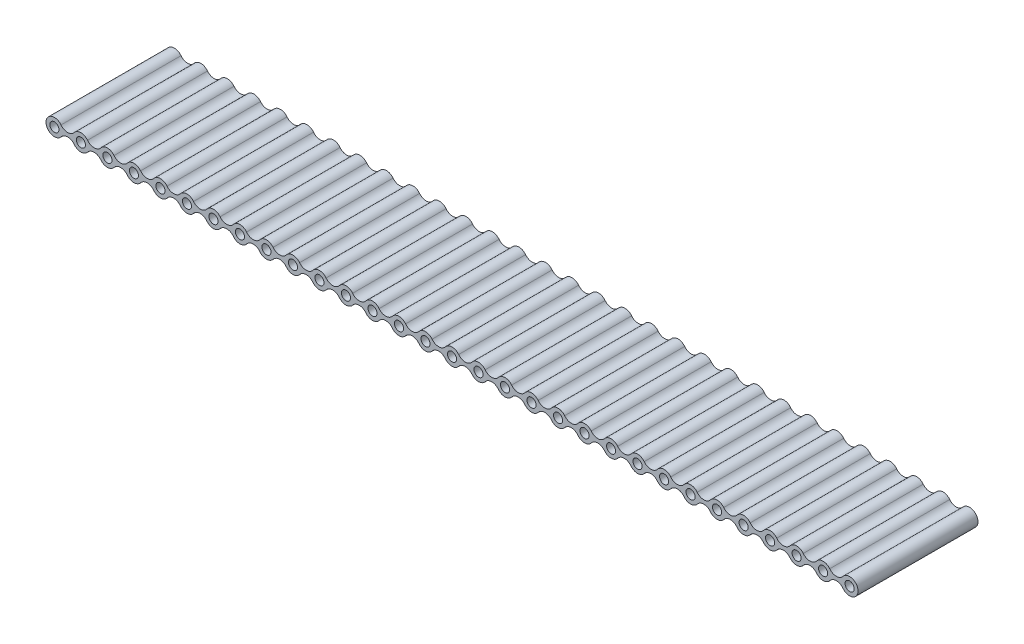
SolidWorks part; units mm, degrees
ref_plane "Front Plane" through (0, 0, 0) normal (0, 0, 1) x (1, 0, 0)
ref_plane "Top Plane" through (0, 0, 0) normal (0, 1, 0) x (1, 0, 0)
ref_plane "Right Plane" through (0, 0, 0) normal (1, 0, 0) x (0, 0, -1)
sketch "Sketch1" plane through (0, 0, 0) normal (0, 0, 1) x (1, 0, 0)
  line L0 (-3.1044, -11.0303) -> (166.8956, -11.0303) construction
  arc A0 (1.3809, 1.075) -> (1.3809, -1.075) centre (0, 0) ccw
  circle A1 centre (0, 0) radius 0.95
  arc A2 (4.1427, -1.075) -> (6.9045, -1.075) centre (5.5236, 0) ccw
  circle A3 centre (5.5236, 0) radius 0.95
  arc A4 (9.6663, -1.075) -> (12.4281, -1.075) centre (11.0472, 0) ccw
  circle A5 centre (11.0472, 0) radius 0.95
  arc A6 (15.1899, -1.075) -> (17.9517, -1.075) centre (16.5708, 0) ccw
  circle A7 centre (16.5708, 0) radius 0.95
  arc A8 (20.7134, -1.075) -> (23.4752, -1.075) centre (22.0943, 0) ccw
  circle A9 centre (22.0943, 0) radius 0.95
  arc A10 (26.237, -1.075) -> (28.9988, -1.075) centre (27.6179, 0) ccw
  circle A11 centre (27.6179, 0) radius 0.95
  arc A12 (31.7606, -1.075) -> (34.5224, -1.075) centre (33.1415, 0) ccw
  circle A13 centre (33.1415, 0) radius 0.95
  arc A14 (37.2842, -1.075) -> (40.046, -1.075) centre (38.6651, 0) ccw
  circle A15 centre (38.6651, 0) radius 0.95
  arc A16 (42.8078, -1.075) -> (45.5696, -1.075) centre (44.1887, 0) ccw
  circle A17 centre (44.1887, 0) radius 0.95
  arc A18 (48.3314, -1.075) -> (51.0932, -1.075) centre (49.7123, 0) ccw
  circle A19 centre (49.7123, 0) radius 0.95
  arc A20 (1.3809, 1.075) -> (4.1427, 1.075) centre (2.7618, 2.15) ccw
  arc A21 (1.3809, -1.075) -> (4.1427, -1.075) centre (2.7618, -2.15) cw
  arc A22 (6.9045, 1.075) -> (9.6663, 1.075) centre (8.2854, 2.15) ccw
  arc A23 (6.9045, -1.075) -> (9.6663, -1.075) centre (8.2854, -2.15) cw
  arc A24 (12.4281, 1.075) -> (15.1899, 1.075) centre (13.809, 2.15) ccw
  arc A25 (12.4281, -1.075) -> (15.1899, -1.075) centre (13.809, -2.15) cw
  arc A26 (17.9517, 1.075) -> (20.7134, 1.075) centre (19.3326, 2.15) ccw
  arc A27 (17.9517, -1.075) -> (20.7134, -1.075) centre (19.3326, -2.15) cw
  arc A28 (23.4752, 1.075) -> (26.237, 1.075) centre (24.8561, 2.15) ccw
  arc A29 (23.4752, -1.075) -> (26.237, -1.075) centre (24.8561, -2.15) cw
  arc A30 (28.9988, 1.075) -> (31.7606, 1.075) centre (30.3797, 2.15) ccw
  arc A31 (28.9988, -1.075) -> (31.7606, -1.075) centre (30.3797, -2.15) cw
  arc A32 (34.5224, 1.075) -> (37.2842, 1.075) centre (35.9033, 2.15) ccw
  arc A33 (34.5224, -1.075) -> (37.2842, -1.075) centre (35.9033, -2.15) cw
  arc A34 (40.046, 1.075) -> (42.8078, 1.075) centre (41.4269, 2.15) ccw
  arc A35 (40.046, -1.075) -> (42.8078, -1.075) centre (41.4269, -2.15) cw
  arc A36 (45.5696, 1.075) -> (48.3314, 1.075) centre (46.9505, 2.15) ccw
  arc A37 (45.5696, -1.075) -> (48.3314, -1.075) centre (46.9505, -2.15) cw
  arc A38 (53.855, -1.075) -> (56.6168, -1.075) centre (55.2359, 0) ccw
  circle A39 centre (55.2359, 0) radius 0.95
  arc A40 (59.3785, -1.075) -> (62.1403, -1.075) centre (60.7594, 0) ccw
  circle A41 centre (60.7594, 0) radius 0.95
  arc A42 (64.9021, -1.075) -> (67.6639, -1.075) centre (66.283, 0) ccw
  circle A43 centre (66.283, 0) radius 0.95
  arc A44 (70.4257, -1.075) -> (73.1875, -1.075) centre (71.8066, 0) ccw
  circle A45 centre (71.8066, 0) radius 0.95
  arc A46 (75.9493, -1.075) -> (78.7111, -1.075) centre (77.3302, 0) ccw
  circle A47 centre (77.3302, 0) radius 0.95
  arc A48 (81.4729, -1.075) -> (84.2347, -1.075) centre (82.8538, 0) ccw
  circle A49 centre (82.8538, 0) radius 0.95
  arc A50 (86.9965, -1.075) -> (89.7583, -1.075) centre (88.3774, 0) ccw
  circle A51 centre (88.3774, 0) radius 0.95
  arc A52 (92.5201, -1.075) -> (95.2819, -1.075) centre (93.901, 0) ccw
  circle A53 centre (93.901, 0) radius 0.95
  arc A54 (98.0436, -1.075) -> (100.8054, -1.075) centre (99.4245, 0) ccw
  circle A55 centre (99.4245, 0) radius 0.95
  arc A56 (103.5672, -1.075) -> (106.329, -1.075) centre (104.9481, 0) ccw
  circle A57 centre (104.9481, 0) radius 0.95
  arc A58 (109.0908, -1.075) -> (111.8526, -1.075) centre (110.4717, 0) ccw
  circle A59 centre (110.4717, 0) radius 0.95
  arc A60 (114.6144, -1.075) -> (117.3762, -1.075) centre (115.9953, 0) ccw
  circle A61 centre (115.9953, 0) radius 0.95
  arc A62 (120.138, -1.075) -> (122.8998, -1.075) centre (121.5189, 0) ccw
  circle A63 centre (121.5189, 0) radius 0.95
  arc A64 (125.6616, -1.075) -> (128.4234, -1.075) centre (127.0425, 0) ccw
  circle A65 centre (127.0425, 0) radius 0.95
  arc A66 (131.1852, -1.075) -> (133.947, -1.075) centre (132.5661, 0) ccw
  circle A67 centre (132.5661, 0) radius 0.95
  arc A68 (136.7087, -1.075) -> (139.4705, -1.075) centre (138.0896, 0) ccw
  circle A69 centre (138.0896, 0) radius 0.95
  arc A70 (142.2323, -1.075) -> (144.9941, -1.075) centre (143.6132, 0) ccw
  circle A71 centre (143.6132, 0) radius 0.95
  arc A72 (147.7559, -1.075) -> (150.5177, -1.075) centre (149.1368, 0) ccw
  circle A73 centre (149.1368, 0) radius 0.95
  arc A74 (153.2795, -1.075) -> (156.0413, -1.075) centre (154.6604, 0) ccw
  circle A75 centre (154.6604, 0) radius 0.95
  arc A76 (51.0932, 1.075) -> (53.855, 1.075) centre (52.4741, 2.15) ccw
  arc A77 (51.0932, -1.075) -> (53.855, -1.075) centre (52.4741, -2.15) cw
  arc A78 (56.6168, 1.075) -> (59.3785, 1.075) centre (57.9977, 2.15) ccw
  arc A79 (56.6168, -1.075) -> (59.3785, -1.075) centre (57.9977, -2.15) cw
  arc A80 (62.1403, 1.075) -> (64.9021, 1.075) centre (63.5212, 2.15) ccw
  arc A81 (62.1403, -1.075) -> (64.9021, -1.075) centre (63.5212, -2.15) cw
  arc A82 (67.6639, 1.075) -> (70.4257, 1.075) centre (69.0448, 2.15) ccw
  arc A83 (67.6639, -1.075) -> (70.4257, -1.075) centre (69.0448, -2.15) cw
  arc A84 (73.1875, 1.075) -> (75.9493, 1.075) centre (74.5684, 2.15) ccw
  arc A85 (73.1875, -1.075) -> (75.9493, -1.075) centre (74.5684, -2.15) cw
  arc A86 (78.7111, 1.075) -> (81.4729, 1.075) centre (80.092, 2.15) ccw
  arc A87 (78.7111, -1.075) -> (81.4729, -1.075) centre (80.092, -2.15) cw
  arc A88 (84.2347, 1.075) -> (86.9965, 1.075) centre (85.6156, 2.15) ccw
  arc A89 (84.2347, -1.075) -> (86.9965, -1.075) centre (85.6156, -2.15) cw
  arc A90 (89.7583, 1.075) -> (92.5201, 1.075) centre (91.1392, 2.15) ccw
  arc A91 (89.7583, -1.075) -> (92.5201, -1.075) centre (91.1392, -2.15) cw
  arc A92 (95.2819, 1.075) -> (98.0436, 1.075) centre (96.6628, 2.15) ccw
  arc A93 (95.2819, -1.075) -> (98.0436, -1.075) centre (96.6628, -2.15) cw
  arc A94 (100.8054, 1.075) -> (103.5672, 1.075) centre (102.1863, 2.15) ccw
  arc A95 (100.8054, -1.075) -> (103.5672, -1.075) centre (102.1863, -2.15) cw
  arc A96 (106.329, 1.075) -> (109.0908, 1.075) centre (107.7099, 2.15) ccw
  arc A97 (106.329, -1.075) -> (109.0908, -1.075) centre (107.7099, -2.15) cw
  arc A98 (111.8526, 1.075) -> (114.6144, 1.075) centre (113.2335, 2.15) ccw
  arc A99 (111.8526, -1.075) -> (114.6144, -1.075) centre (113.2335, -2.15) cw
  arc A100 (117.3762, 1.075) -> (120.138, 1.075) centre (118.7571, 2.15) ccw
  arc A101 (117.3762, -1.075) -> (120.138, -1.075) centre (118.7571, -2.15) cw
  arc A102 (122.8998, 1.075) -> (125.6616, 1.075) centre (124.2807, 2.15) ccw
  arc A103 (122.8998, -1.075) -> (125.6616, -1.075) centre (124.2807, -2.15) cw
  arc A104 (128.4234, 1.075) -> (131.1852, 1.075) centre (129.8043, 2.15) ccw
  arc A105 (128.4234, -1.075) -> (131.1852, -1.075) centre (129.8043, -2.15) cw
  arc A106 (133.947, 1.075) -> (136.7087, 1.075) centre (135.3279, 2.15) ccw
  arc A107 (133.947, -1.075) -> (136.7087, -1.075) centre (135.3279, -2.15) cw
  arc A108 (139.4705, 1.075) -> (142.2323, 1.075) centre (140.8514, 2.15) ccw
  arc A109 (139.4705, -1.075) -> (142.2323, -1.075) centre (140.8514, -2.15) cw
  arc A110 (144.9941, 1.075) -> (147.7559, 1.075) centre (146.375, 2.15) ccw
  arc A111 (144.9941, -1.075) -> (147.7559, -1.075) centre (146.375, -2.15) cw
  arc A112 (150.5177, 1.075) -> (153.2795, 1.075) centre (151.8986, 2.15) ccw
  arc A113 (150.5177, -1.075) -> (153.2795, -1.075) centre (151.8986, -2.15) cw
  arc A114 (4.1427, 1.075) -> (4.1427, -1.075) centre (5.5236, 0) ccw construction
  arc A115 (1.3809, -1.075) -> (1.3809, 1.075) centre (0, 0) ccw construction
  arc A116 (6.9045, -1.075) -> (6.9045, 1.075) centre (5.5236, 0) ccw construction
  arc A117 (6.9045, 1.075) -> (4.1427, 1.075) centre (5.5236, 0) ccw
  arc A118 (9.6663, 1.075) -> (9.6663, -1.075) centre (11.0472, 0) ccw construction
  arc A119 (12.4281, -1.075) -> (12.4281, 1.075) centre (11.0472, 0) ccw construction
  arc A120 (12.4281, 1.075) -> (9.6663, 1.075) centre (11.0472, 0) ccw
  arc A121 (15.1899, 1.075) -> (15.1899, -1.075) centre (16.5708, 0) ccw construction
  arc A122 (17.9517, -1.075) -> (17.9517, 1.075) centre (16.5708, 0) ccw construction
  arc A123 (17.9517, 1.075) -> (15.1899, 1.075) centre (16.5708, 0) ccw
  arc A124 (20.7134, 1.075) -> (20.7134, -1.075) centre (22.0943, 0) ccw construction
  arc A125 (23.4752, -1.075) -> (23.4752, 1.075) centre (22.0943, 0) ccw construction
  arc A126 (23.4752, 1.075) -> (20.7134, 1.075) centre (22.0943, 0) ccw
  arc A127 (26.237, 1.075) -> (26.237, -1.075) centre (27.6179, 0) ccw construction
  arc A128 (28.9988, -1.075) -> (28.9988, 1.075) centre (27.6179, 0) ccw construction
  arc A129 (28.9988, 1.075) -> (26.237, 1.075) centre (27.6179, 0) ccw
  arc A130 (31.7606, 1.075) -> (31.7606, -1.075) centre (33.1415, 0) ccw construction
  arc A131 (34.5224, -1.075) -> (34.5224, 1.075) centre (33.1415, 0) ccw construction
  arc A132 (34.5224, 1.075) -> (31.7606, 1.075) centre (33.1415, 0) ccw
  arc A133 (37.2842, 1.075) -> (37.2842, -1.075) centre (38.6651, 0) ccw construction
  arc A134 (40.046, -1.075) -> (40.046, 1.075) centre (38.6651, 0) ccw construction
  arc A135 (40.046, 1.075) -> (37.2842, 1.075) centre (38.6651, 0) ccw
  arc A136 (42.8078, 1.075) -> (42.8078, -1.075) centre (44.1887, 0) ccw construction
  arc A137 (45.5696, -1.075) -> (45.5696, 1.075) centre (44.1887, 0) ccw construction
  arc A138 (45.5696, 1.075) -> (42.8078, 1.075) centre (44.1887, 0) ccw
  arc A139 (48.3314, 1.075) -> (48.3314, -1.075) centre (49.7123, 0) ccw construction
  arc A140 (51.0932, -1.075) -> (51.0932, 1.075) centre (49.7123, 0) ccw construction
  arc A141 (51.0932, 1.075) -> (48.3314, 1.075) centre (49.7123, 0) ccw
  arc A142 (53.855, 1.075) -> (53.855, -1.075) centre (55.2359, 0) ccw construction
  arc A143 (56.6168, -1.075) -> (56.6168, 1.075) centre (55.2359, 0) ccw construction
  arc A144 (56.6168, 1.075) -> (53.855, 1.075) centre (55.2359, 0) ccw
  arc A145 (59.3785, 1.075) -> (59.3785, -1.075) centre (60.7594, 0) ccw construction
  arc A146 (62.1403, -1.075) -> (62.1403, 1.075) centre (60.7594, 0) ccw construction
  arc A147 (62.1403, 1.075) -> (59.3785, 1.075) centre (60.7594, 0) ccw
  arc A148 (64.9021, 1.075) -> (64.9021, -1.075) centre (66.283, 0) ccw construction
  arc A149 (67.6639, -1.075) -> (67.6639, 1.075) centre (66.283, 0) ccw construction
  arc A150 (67.6639, 1.075) -> (64.9021, 1.075) centre (66.283, 0) ccw
  arc A151 (70.4257, 1.075) -> (70.4257, -1.075) centre (71.8066, 0) ccw construction
  arc A152 (73.1875, -1.075) -> (73.1875, 1.075) centre (71.8066, 0) ccw construction
  arc A153 (73.1875, 1.075) -> (70.4257, 1.075) centre (71.8066, 0) ccw
  arc A154 (75.9493, 1.075) -> (75.9493, -1.075) centre (77.3302, 0) ccw construction
  arc A155 (78.7111, -1.075) -> (78.7111, 1.075) centre (77.3302, 0) ccw construction
  arc A156 (78.7111, 1.075) -> (75.9493, 1.075) centre (77.3302, 0) ccw
  arc A157 (81.4729, 1.075) -> (81.4729, -1.075) centre (82.8538, 0) ccw construction
  arc A158 (84.2347, -1.075) -> (84.2347, 1.075) centre (82.8538, 0) ccw construction
  arc A159 (84.2347, 1.075) -> (81.4729, 1.075) centre (82.8538, 0) ccw
  arc A160 (86.9965, 1.075) -> (86.9965, -1.075) centre (88.3774, 0) ccw construction
  arc A161 (89.7583, -1.075) -> (89.7583, 1.075) centre (88.3774, 0) ccw construction
  arc A162 (89.7583, 1.075) -> (86.9965, 1.075) centre (88.3774, 0) ccw
  arc A163 (92.5201, 1.075) -> (92.5201, -1.075) centre (93.901, 0) ccw construction
  arc A164 (95.2819, -1.075) -> (95.2819, 1.075) centre (93.901, 0) ccw construction
  arc A165 (95.2819, 1.075) -> (92.5201, 1.075) centre (93.901, 0) ccw
  arc A166 (98.0436, 1.075) -> (98.0436, -1.075) centre (99.4245, 0) ccw construction
  arc A167 (100.8054, -1.075) -> (100.8054, 1.075) centre (99.4245, 0) ccw construction
  arc A168 (100.8054, 1.075) -> (98.0436, 1.075) centre (99.4245, 0) ccw
  arc A169 (103.5672, 1.075) -> (103.5672, -1.075) centre (104.9481, 0) ccw construction
  arc A170 (106.329, -1.075) -> (106.329, 1.075) centre (104.9481, 0) ccw construction
  arc A171 (106.329, 1.075) -> (103.5672, 1.075) centre (104.9481, 0) ccw
  arc A172 (109.0908, 1.075) -> (109.0908, -1.075) centre (110.4717, 0) ccw construction
  arc A173 (111.8526, -1.075) -> (111.8526, 1.075) centre (110.4717, 0) ccw construction
  arc A174 (111.8526, 1.075) -> (109.0908, 1.075) centre (110.4717, 0) ccw
  arc A175 (114.6144, 1.075) -> (114.6144, -1.075) centre (115.9953, 0) ccw construction
  arc A176 (117.3762, -1.075) -> (117.3762, 1.075) centre (115.9953, 0) ccw construction
  arc A177 (117.3762, 1.075) -> (114.6144, 1.075) centre (115.9953, 0) ccw
  arc A178 (120.138, 1.075) -> (120.138, -1.075) centre (121.5189, 0) ccw construction
  arc A179 (122.8998, -1.075) -> (122.8998, 1.075) centre (121.5189, 0) ccw construction
  arc A180 (122.8998, 1.075) -> (120.138, 1.075) centre (121.5189, 0) ccw
  arc A181 (125.6616, 1.075) -> (125.6616, -1.075) centre (127.0425, 0) ccw construction
  arc A182 (128.4234, -1.075) -> (128.4234, 1.075) centre (127.0425, 0) ccw construction
  arc A183 (128.4234, 1.075) -> (125.6616, 1.075) centre (127.0425, 0) ccw
  arc A184 (131.1852, 1.075) -> (131.1852, -1.075) centre (132.5661, 0) ccw construction
  arc A185 (133.947, -1.075) -> (133.947, 1.075) centre (132.5661, 0) ccw construction
  arc A186 (133.947, 1.075) -> (131.1852, 1.075) centre (132.5661, 0) ccw
  arc A187 (136.7087, 1.075) -> (136.7087, -1.075) centre (138.0896, 0) ccw construction
  arc A188 (139.4705, -1.075) -> (139.4705, 1.075) centre (138.0896, 0) ccw construction
  arc A189 (139.4705, 1.075) -> (136.7087, 1.075) centre (138.0896, 0) ccw
  arc A190 (142.2323, 1.075) -> (142.2323, -1.075) centre (143.6132, 0) ccw construction
  arc A191 (144.9941, -1.075) -> (144.9941, 1.075) centre (143.6132, 0) ccw construction
  arc A192 (144.9941, 1.075) -> (142.2323, 1.075) centre (143.6132, 0) ccw
  arc A193 (147.7559, 1.075) -> (147.7559, -1.075) centre (149.1368, 0) ccw construction
  arc A194 (150.5177, -1.075) -> (150.5177, 1.075) centre (149.1368, 0) ccw construction
  arc A195 (150.5177, 1.075) -> (147.7559, 1.075) centre (149.1368, 0) ccw
  arc A196 (153.2795, 1.075) -> (153.2795, -1.075) centre (154.6604, 0) ccw construction
  arc A197 (161.5649, 1.075) -> (158.8031, 1.075) centre (160.184, 0) ccw
  circle A198 centre (160.184, 0) radius 0.95
  arc A199 (166.9576, 1.2247) -> (164.3267, 1.075) centre (165.7076, 0) ccw
  circle A200 centre (165.7076, 0) radius 0.95
  arc A205 (156.0413, 1.075) -> (158.8031, 1.075) centre (157.4222, 2.15) ccw
  arc A206 (156.0413, -1.075) -> (158.8031, -1.075) centre (157.4222, -2.15) cw
  arc A207 (161.5649, 1.075) -> (164.3267, 1.075) centre (162.9458, 2.15) ccw
  arc A208 (161.5649, -1.075) -> (164.3267, -1.075) centre (162.9458, -2.15) cw
  arc A213 (166.9576, -1.2247) -> (166.9576, 1.2247) centre (165.7076, 0) ccw
  arc A218 (164.3267, 1.075) -> (164.3267, -1.075) centre (165.7076, 0) ccw construction
  arc A219 (164.3267, -1.075) -> (166.9576, -1.2247) centre (165.7076, 0) ccw
  arc A220 (158.8031, 1.075) -> (158.8031, -1.075) centre (160.184, 0) ccw construction
  arc A221 (158.8031, -1.075) -> (161.5649, -1.075) centre (160.184, 0) ccw
  arc A222 (156.0413, -1.075) -> (156.0413, 1.075) centre (154.6604, 0) ccw construction
  arc A223 (156.0413, 1.075) -> (153.2795, 1.075) centre (154.6604, 0) ccw
  point P1 (2.7618, 0.4)
  point P6 (2.7618, -0.4)
  point P87 (167.2388, 1.075)
  point P89 (167.3764, -1.075)
  point P92 (173.2101, -2.3455)
  point P95 (0, 0)
  point P98 (0, 0)
  point P104 (166.9576, 1.2247)
  point P134 (169.4659, 0)
  point P143 (169.7113, -0.9463)
  point P261 (169.5197, 0)
  point P274 (169.6347, 0.9723)
  dimension "D1" = 0.8
  dimension "D2" = 1.9
  dimension "D4" = 0.8
  dimension "D5" = 30
  dimension "D6" = 170
  dimension "D3" = 31
extrude "Boss-Extrude1" add sketch "Sketch1" along normal blind 25
